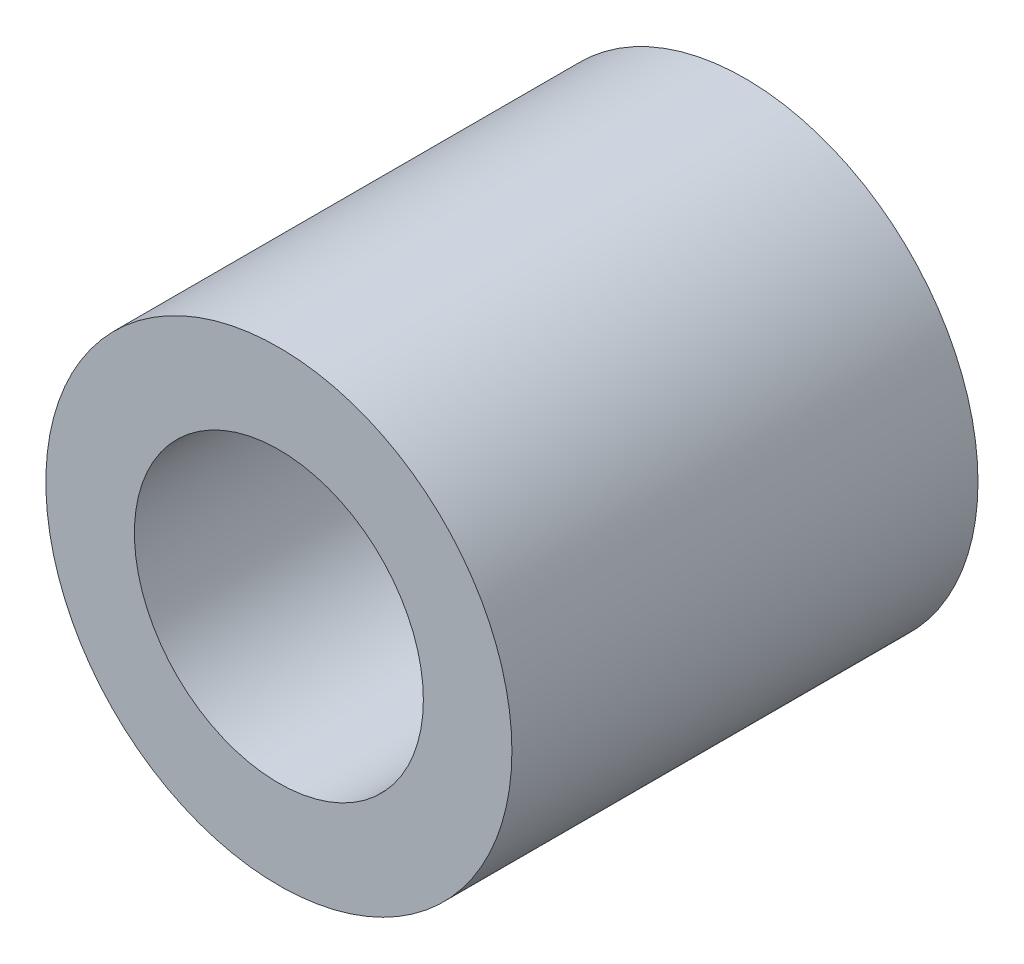
SolidWorks part; units mm, degrees
ref_plane "Front Plane" through (0, 0, 0) normal (0, 0, 1) x (1, 0, 0)
ref_plane "Top Plane" through (0, 0, 0) normal (0, 1, 0) x (1, 0, 0)
ref_plane "Right Plane" through (0, 0, 0) normal (1, 0, 0) x (0, 0, -1)
sketch "Sketch1" plane through (0, 0, 0) normal (0, 0, 1) x (1, 0, 0)
  circle A0 centre (0, 0) radius 1.55
  circle A1 centre (0, 0) radius 2.5
  dimension "D1" = 3.1
  dimension "D2" = 5
extrude "Boss-Extrude1" add sketch "Sketch1" along normal blind 5
